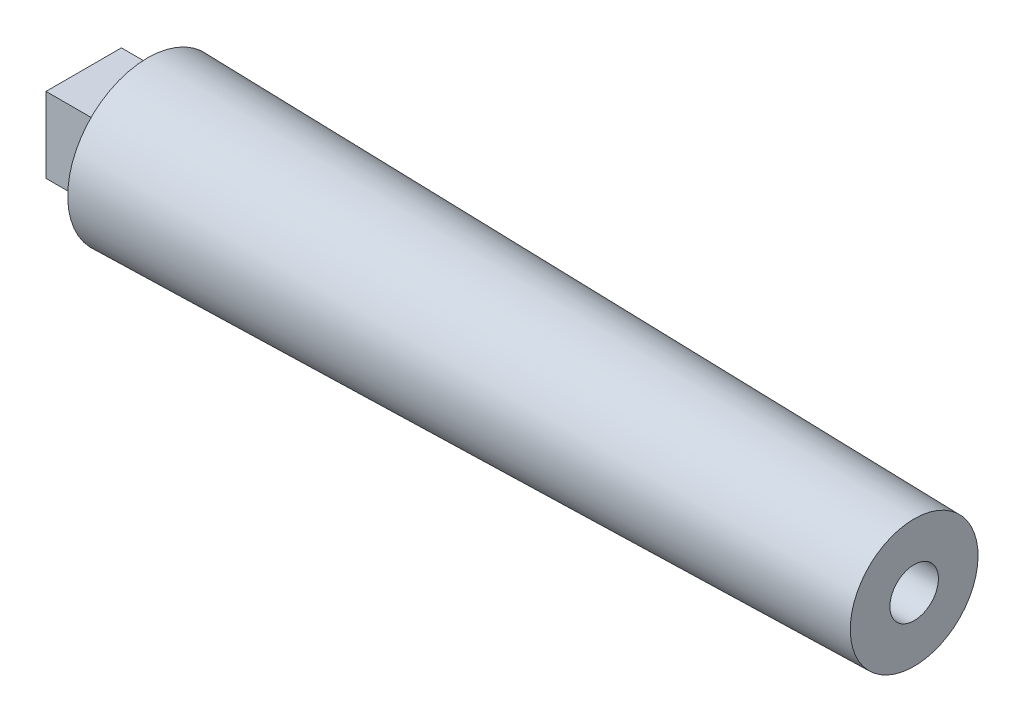
SolidWorks part; units mm, degrees
ref_plane "Front Plane" through (0, 0, 0) normal (0, 0, 1) x (1, 0, 0)
ref_plane "Top Plane" through (0, 0, 0) normal (0, 1, 0) x (1, 0, 0)
ref_plane "Right Plane" through (0, 0, 0) normal (1, 0, 0) x (0, 0, -1)
sketch "Sketch1" plane through (0, 0, 0) normal (0, 0, 1) x (1, 0, 0)
  line L0 (0, 12.7) -> (0, 0)
  line L1 (0, 0) -> (-152.4, 0)
  line L2 (-152.4, 0) -> (-152.4, 15.875)
  line L3 (-152.4, 15.875) -> (0, 12.7)
  dimension "D1" = 12.7
  dimension "D2" = 15.875
  dimension "D3" = 152.4
revolve "Revolve1" add sketch "Sketch1" angle 360 about L1
sketch "Sketch2" plane through (-152.4, 0, 0) normal (-1, 0, 0) x (0, 0, 1)
  line L1 (-7.493, -7.493) -> (7.493, -7.493)
  line L2 (-7.493, -7.493) -> (-7.493, 7.493)
  line L3 (-7.493, 7.493) -> (7.493, 7.493)
  line L4 (7.493, -7.493) -> (7.493, 7.493)
  line L5 (-7.493, -7.493) -> (7.493, 7.493) construction
  line L6 (-7.493, 7.493) -> (7.493, -7.493) construction
  point P0 (0, 0)
  dimension "D1" = 14.986
  dimension "D2" = 14.986
extrude "Boss-Extrude1" add sketch "Sketch2" along normal blind 12.7
sketch "Sketch3" plane through (0, 0, 0) normal (1, 0, 0) x (0, 0, -1)
  circle A0 centre (0, 0) radius 4.826
  dimension "D1" = 9.652
extrude "Cut-Extrude1" cut sketch "Sketch3" against normal blind 25.4
